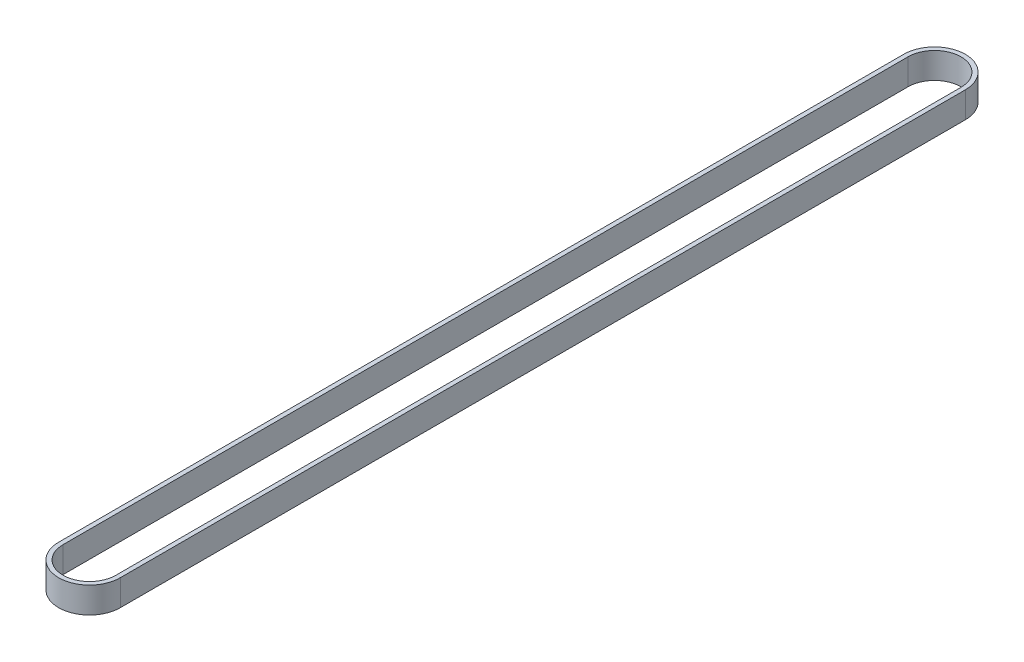
SolidWorks part; units mm, degrees
material "天然橡胶"
ref_plane "前视基准面" through (0, 0, 0) normal (0, 0, 1) x (1, 0, 0)
ref_plane "上视基准面" through (0, 0, 0) normal (0, 1, 0) x (1, 0, 0)
ref_plane "右视基准面" through (0, 0, 0) normal (1, 0, 0) x (0, 0, -1)
other "Configuration Table"
sketch "草图1" plane through (0, 0, 0) normal (0, 1, 0) x (1, 0, 0)
  line L0 (0, -97.55) -> (0, 97.55) construction
  line L1 (-7.11, -97.55) -> (-7.11, 97.55)
  line L2 (7.11, -97.55) -> (7.11, 97.55)
  line L3 (0, -97.55) -> (0, 97.55) construction
  line L4 (-6.11, -97.55) -> (-6.11, 97.55)
  line L5 (6.11, -97.55) -> (6.11, 97.55)
  arc A0 (-7.11, -97.55) -> (7.11, -97.55) centre (0, -97.55) ccw
  arc A1 (7.11, 97.55) -> (-7.11, 97.55) centre (0, 97.55) ccw
  arc A2 (-6.11, -97.55) -> (6.11, -97.55) centre (0, -97.55) ccw
  arc A3 (6.11, 97.55) -> (-6.11, 97.55) centre (0, 97.55) ccw
  point P2 (0, 0)
  point P9 (0, 0)
  dimension "D3" = 6.11
  dimension "D4" = 7.11
  dimension "D1" = 195.1
  dimension "D2" = 195.1
extrude "凸台-拉伸1" add sketch "草图1" along normal blind 6
